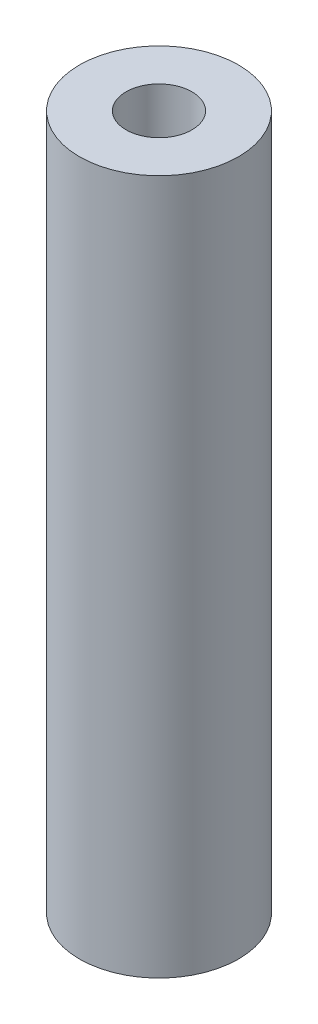
SolidWorks part; units mm, degrees
ref_plane "Front Plane" through (0, 0, 0) normal (0, 0, 1) x (1, 0, 0)
ref_plane "Top Plane" through (0, 0, 0) normal (0, 1, 0) x (1, 0, 0)
ref_plane "Right Plane" through (0, 0, 0) normal (1, 0, 0) x (0, 0, -1)
sketch "Sketch1" plane through (0, 0, 0) normal (0, 1, 0) x (1, 0, 0)
  circle A0 centre (0, 0) radius 7.415
  circle A1 centre (0, 0) radius 3.075
extrude "Boss-Extrude1" add sketch "Sketch1" along normal blind 64.78
